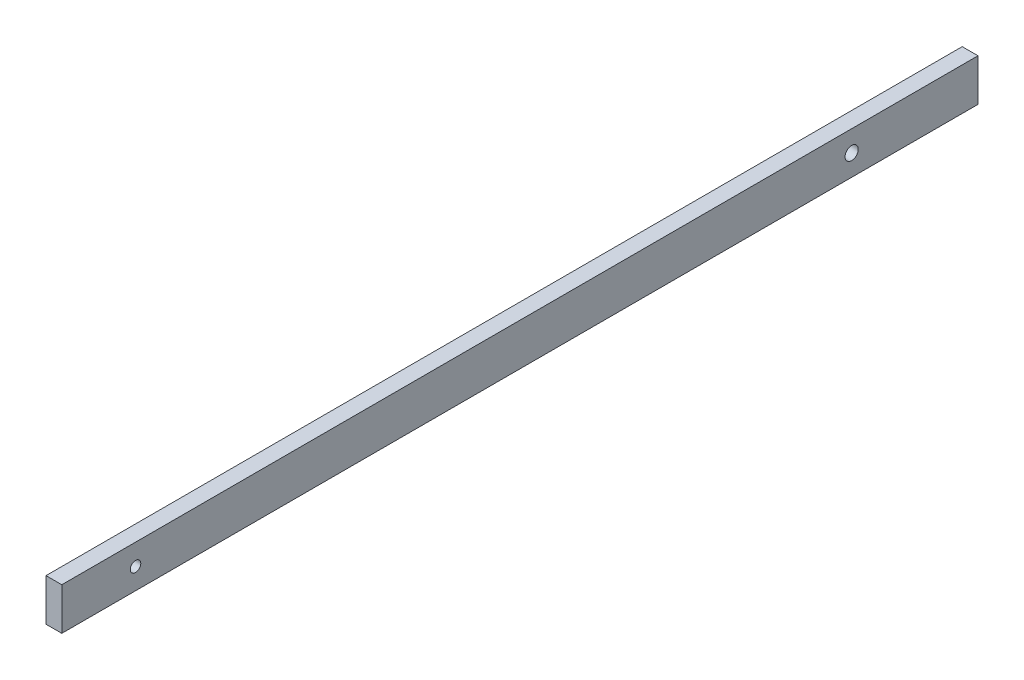
SolidWorks part; units mm, degrees
material "Pine"
ref_plane "Front Plane" through (0, 0, 0) normal (0, 0, 1) x (1, 0, 0)
ref_plane "Top Plane" through (0, 0, 0) normal (0, 1, 0) x (1, 0, 0)
ref_plane "Right Plane" through (0, 0, 0) normal (1, 0, 0) x (0, 0, -1)
sketch "Sketch1" plane through (0, 0, 0) normal (0, 1, 0) x (1, 0, 0)
  line L1 (-9.525, -552.45) -> (9.525, -552.45)
  line L2 (-9.525, -552.45) -> (-9.525, 552.45)
  line L3 (-9.525, 552.45) -> (9.525, 552.45)
  line L4 (9.525, -552.45) -> (9.525, 552.45)
  line L5 (-9.525, -552.45) -> (9.525, 552.45) construction
  line L6 (-9.525, 552.45) -> (9.525, -552.45) construction
  point P0 (0, 0)
  dimension "D1" = 1104.9
  dimension "D2" = 19.05
extrude "Boss-Extrude1" add sketch "Sketch1" against normal blind 50.8
sketch "Sketch2" plane through (9.525, 0, 0) normal (1, 0, 0) x (0, 0, -1)
  line L0 (552.45, -50.8) -> (552.45, 0) construction
  line L1 (-552.45, -50.8) -> (-552.45, 0) construction
  line L2 (-552.45, 0) -> (552.45, 0) construction
  line L3 (-298.45, 0) -> (-260.35, 0) construction
  line L4 (-298.45, 0) -> (-298.45, -19.05) construction
  line L5 (-298.45, -19.05) -> (-260.35, -19.05) construction
  line L6 (-260.35, 0) -> (-260.35, -19.05) construction
  line L7 (-552.45, -50.8) -> (552.45, -50.8) construction
  circle A0 centre (400.05, -25.4) radius 7.9375
  circle A1 centre (-463.55, -25.4) radius 6.35
  point P5 (552.45, -25.4)
  dimension "D1" = 15.875
  dimension "D7" = 12.7
  dimension "D2" = 152.4
  dimension "D3" = 88.9
  dimension "D4" = 31.75
  dimension "D5" = 254
  dimension "D6" = 38.1
extrude "Cut-Extrude1" cut sketch "Sketch2" against normal through all
